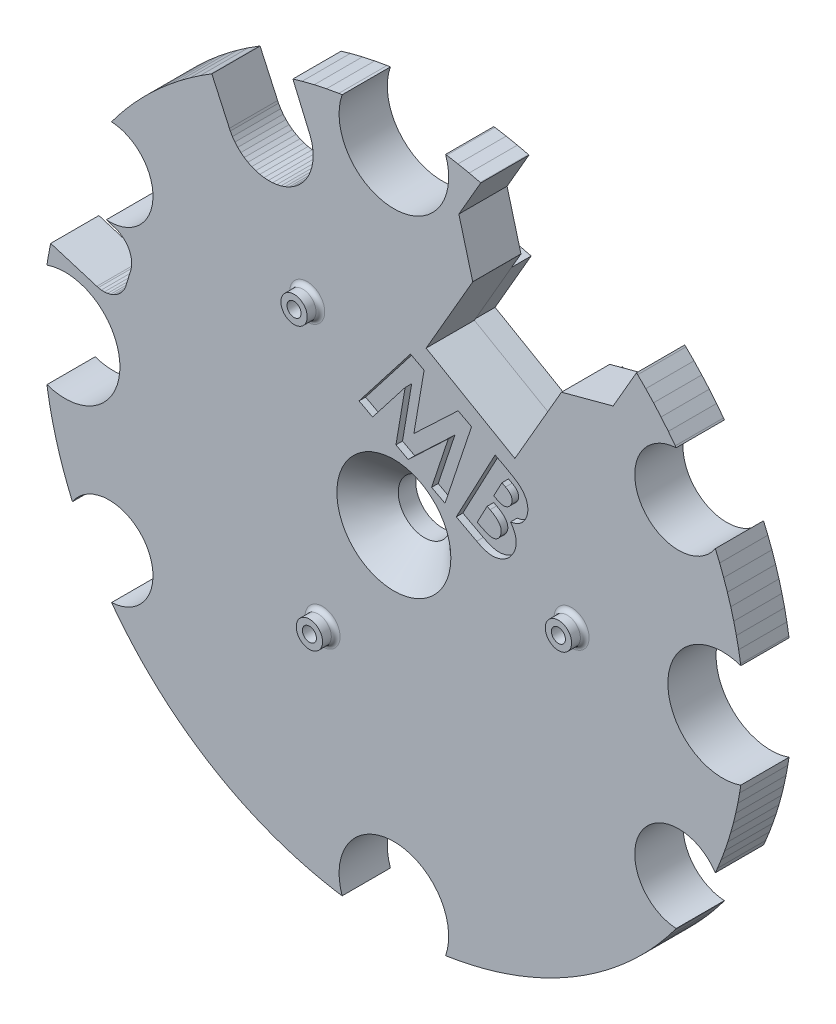
SolidWorks part; units mm, degrees
ref_plane "Płaszczyzna przednia" through (0, 0, 0) normal (0, 0, 1) x (1, 0, 0)
ref_plane "Płaszczyzna górna" through (0, 0, 0) normal (0, 1, 0) x (1, 0, 0)
ref_plane "Płaszczyzna prawa" through (0, 0, 0) normal (1, 0, 0) x (0, 0, -1)
sketch "mandaryna sloty " plane through (0, 0, 0) normal (0, 0, 1) x (1, 0, 0)
  line L0 (16.267, -5.639) -> (49.1732, -24.6374)
  line L1 (49.1732, 24.6374) -> (16.267, 5.639)
  line L2 (13.017, 11.2682) -> (45.9232, 30.2665)
  line L3 (3.25, 54.9039) -> (3.25, 16.9072)
  line L4 (-3.25, 16.9072) -> (-3.25, 54.9039)
  line L5 (-45.9232, 30.2665) -> (-13.017, 11.2682)
  line L6 (37.2705, 55.4531) -> (37.2682, 55.4521) construction
  line L7 (47.1514, 32.7352) -> (37.2705, 55.4531) construction
  line L8 (13.142, 11.0517) -> (46.0605, 30.0571) construction
  line L9 (3, 54.9181) -> (3, 16.9072) construction
  line L10 (29.3889, 60.0012) -> (29.3886, 60.0037) construction
  line L11 (49.0605, 24.861) -> (16.142, 5.8555) construction
  line L12 (60.689, -29.3106) -> (66.5056, -28.6485) construction
  line L13 (16.142, -5.8555) -> (49.0605, -24.861) construction
  line L14 (-16.267, 5.639) -> (-49.1732, 24.6374)
  line L15 (-49.1732, -24.6374) -> (-16.267, -5.639)
  line L16 (46.0605, -30.0571) -> (13.142, -11.0517) construction
  line L17 (58.0631, -43.2712) -> (55.7282, -37.9029) construction
  line L18 (3, -16.9072) -> (3, -54.9181) construction
  line L19 (-13.017, -11.2682) -> (-45.9232, -30.2665)
  line L20 (-3.25, -54.9039) -> (-3.25, -16.9072)
  line L21 (3.25, -16.9072) -> (3.25, -54.9039)
  line L22 (45.9232, -30.2665) -> (13.017, -11.2682)
  line L23 (-29.3886, -60.0037) -> (-4.7738, -57.2019) construction
  line L24 (-29.3889, -60.0012) -> (-29.3886, -60.0037) construction
  line L25 (-37.2705, -55.4531) -> (-37.2682, -55.4521) construction
  line L26 (-47.1514, -32.7352) -> (-37.2705, -55.4531) construction
  line L27 (-60.689, 29.3106) -> (-66.5056, 28.6485) construction
  line L28 (-16.142, 5.8555) -> (-49.0605, 24.861) construction
  line L29 (-46.0605, 30.0571) -> (-13.142, 11.0517) construction
  line L30 (-58.0631, 43.2712) -> (-55.7282, 37.9029) construction
  line L31 (-3, 16.9072) -> (-3, 54.9181) construction
  line L37 (15.3138, 52.8251) -> (7.087, 38.5758)
  line L38 (7.087, 38.5758) -> (27.6707, 26.6918)
  line L39 (27.6707, 26.6918) -> (36.1779, 41.4266)
  circle A0 centre (0, 0) radius 85 construction
  circle A1 centre (0, 0) radius 6 construction
  arc A2 (16.267, 5.639) -> (16.267, -5.639) centre (19.5227, 0) ccw
  arc A3 (3.25, 16.9072) -> (13.017, 11.2682) centre (9.7614, 16.9072) ccw
  arc A4 (-13.017, 11.2682) -> (-3.25, 16.9072) centre (-9.7614, 16.9072) ccw
  arc A5 (46.3174, 30.2054) -> (47.1514, 32.7352) centre (45.3174, 31.9375) ccw construction
  arc A6 (3, 16.9072) -> (13.142, 11.0517) centre (9.7614, 16.9072) ccw construction
  arc A7 (29.3889, 60.0012) -> (31.8898, 56.2177) centre (34.3568, 60.5667) ccw construction
  arc A8 (32.7411, 55.7262) -> (31.8898, 56.2177) centre (0, 0) ccw construction
  arc A9 (32.7411, 55.7262) -> (37.2682, 55.4521) centre (35.2739, 60.0372) ccw construction
  arc A10 (73.76, 25.3667) -> (59.3035, 30.7748) centre (64.3035, 22.1146) ccw construction
  arc A11 (74.9885, -21.4645) -> (73.76, 25.3667) centre (0, 0) ccw construction
  arc A12 (66.5056, -28.6485) -> (74.9885, -21.4645) centre (65.3746, -18.7127) ccw construction
  arc A13 (54.558, -28.035) -> (60.689, -29.3106) centre (59.558, -19.3747) ccw construction
  arc A14 (16.142, 5.8555) -> (16.142, -5.8555) centre (19.5227, 0) ccw construction
  arc A15 (-16.267, -5.639) -> (-16.267, 5.639) centre (-19.5227, 0) ccw
  arc A16 (55.7282, -37.9029) -> (51.558, -33.2312) centre (46.558, -41.8914) ccw construction
  arc A17 (56.0831, -54.2097) -> (58.0631, -43.2712) centre (48.8929, -47.2597) ccw construction
  arc A18 (14.9118, -76.5613) -> (56.0831, -54.2097) centre (0, 0) ccw construction
  arc A19 (3, -66.7458) -> (14.9118, -76.5613) centre (13, -66.7458) ccw construction
  arc A20 (13.142, -11.0517) -> (3, -16.9072) centre (9.7614, -16.9072) ccw construction
  arc A21 (-3.25, -16.9072) -> (-13.017, -11.2682) centre (-9.7614, -16.9072) ccw
  arc A22 (-29.3889, -60.0012) -> (-31.8898, -56.2177) centre (-34.3568, -60.5667) ccw construction
  arc A23 (-32.7411, -55.7262) -> (-31.8898, -56.2177) centre (0, 0) ccw construction
  arc A24 (-32.7411, -55.7262) -> (-37.2682, -55.4521) centre (-35.2739, -60.0372) ccw construction
  arc A25 (-46.3174, -30.2054) -> (-47.1514, -32.7352) centre (-45.3174, -31.9375) ccw construction
  arc A26 (-3, -16.9072) -> (-13.142, -11.0517) centre (-9.7614, -16.9072) ccw construction
  arc A27 (13.017, -11.2682) -> (3.25, -16.9072) centre (9.7614, -16.9072) ccw
  arc A28 (3.25, -54.9039) -> (45.9232, -30.2665) centre (0, 0) ccw
  arc A29 (45.9232, 30.2665) -> (36.1779, 41.4266) centre (0, 0) ccw
  arc A30 (-73.76, -25.3667) -> (-59.3035, -30.7748) centre (-64.3035, -22.1146) ccw construction
  arc A31 (-74.9885, 21.4645) -> (-73.76, -25.3667) centre (0, 0) ccw construction
  arc A32 (-66.5056, 28.6485) -> (-74.9885, 21.4645) centre (-65.3746, 18.7127) ccw construction
  arc A33 (-54.558, 28.035) -> (-60.689, 29.3106) centre (-59.558, 19.3747) ccw construction
  arc A34 (-16.142, -5.8555) -> (-16.142, 5.8555) centre (-19.5227, 0) ccw construction
  arc A35 (-3.25, 54.9039) -> (-45.9232, 30.2665) centre (0, 0) ccw
  arc A36 (-49.1732, 24.6374) -> (-49.1732, -24.6374) centre (0, 0) ccw
  arc A37 (-45.9232, -30.2665) -> (-3.25, -54.9039) centre (0, 0) ccw
  arc A38 (49.1732, -24.6374) -> (49.1732, 24.6374) centre (0, 0) ccw
  arc A39 (-55.7282, 37.9029) -> (-51.558, 33.2312) centre (-46.558, 41.8914) ccw construction
  arc A40 (-56.0831, 54.2097) -> (-58.0631, 43.2712) centre (-48.8929, 47.2597) ccw construction
  arc A41 (-14.9118, 76.5613) -> (-56.0831, 54.2097) centre (0, 0) ccw construction
  arc A42 (-3, 66.7458) -> (-14.9118, 76.5613) centre (-13, 66.7458) ccw construction
  arc A43 (-13.142, 11.0517) -> (-3, 16.9072) centre (-9.7614, 16.9072) ccw construction
  arc A44 (15.3138, 52.8251) -> (3.25, 54.9039) centre (0, 0) ccw
extrude "sloty_mandaryna" add sketch "mandaryna sloty " along normal blind 5
sketch "szkic Koslau" plane through (0, 0, 0) normal (0, 0, 1) x (1, 0, 0)
  line L0 (0, 0) -> (75, 0) construction
  line L1 (0, 0) -> (83.812, 48.3889) construction
  line L2 (0, 0) -> (80.3963, -46.4168) construction
  line L3 (-16.27, -28.1805) -> (0, 0) construction
  line L4 (0, 0) -> (40.54, 0) construction
  line L5 (-19.77, 34.2427) -> (0, 0) construction
  line L6 (-65.6121, 27.5218) -> (-63.6026, 26.9075)
  line L664 (-41.5257, 68.3953) -> (-41.7981, 68.2351)
  line L665 (-41.7981, 68.2351) -> (-44.2022, 66.7029)
  line L666 (-44.2022, 66.7029) -> (-46.5503, 65.0859)
  line L667 (-46.5503, 65.0859) -> (-48.8393, 63.3864)
  line L668 (-48.8393, 63.3864) -> (-51.0663, 61.6064)
  line L669 (-51.0663, 61.6064) -> (-53.2284, 59.7481)
  line L670 (-53.2284, 59.7481) -> (-55.323, 57.8141)
  line L671 (-55.323, 57.8141) -> (-57.3474, 55.8066)
  line L672 (-57.3474, 55.8066) -> (-59.299, 53.7284)
  line L673 (-59.299, 53.7284) -> (-61.1753, 51.5819)
  line L674 (-61.1753, 51.5819) -> (-62.974, 49.3699)
  line L675 (-62.974, 49.3699) -> (-64.3985, 47.4847)
  line L684 (-63.6026, 26.9075) -> (-63.2677, 26.8051)
  line L685 (-63.2677, 26.8051) -> (-62.6302, 26.5146)
  line L686 (-62.6302, 26.5146) -> (-62.0361, 26.1433)
  line L687 (-62.0361, 26.1433) -> (-61.4956, 25.6977)
  line L688 (-61.4956, 25.6977) -> (-61.0178, 25.1854)
  line L689 (-61.0178, 25.1854) -> (-60.611, 24.6151)
  line L690 (-60.611, 24.6151) -> (-60.2822, 23.9966)
  line L691 (-60.2822, 23.9966) -> (-60.0368, 23.3404)
  line L692 (-60.0368, 23.3404) -> (-59.8793, 22.6578)
  line L693 (-59.8793, 22.6578) -> (-59.8121, 21.9605)
  line L694 (-59.8121, 21.9605) -> (-59.8366, 21.2604)
  line L695 (-59.8366, 21.2604) -> (-59.9522, 20.5695)
  line L696 (-59.9522, 20.5695) -> (-60.0546, 20.2345)
  line L697 (-60.0546, 20.2345) -> (-61.0884, 16.853)
  line L698 (-61.0884, 16.853) -> (-61.1908, 16.5181)
  line L699 (-61.1908, 16.5181) -> (-61.4813, 15.8806)
  line L700 (-61.4813, 15.8806) -> (-61.8525, 15.2866)
  line L701 (-61.8525, 15.2866) -> (-62.2981, 14.746)
  line L702 (-62.2981, 14.746) -> (-62.8105, 14.2682)
  line L703 (-62.8105, 14.2682) -> (-63.3808, 13.8614)
  line L704 (-63.3808, 13.8614) -> (-63.9993, 13.5326)
  line L705 (-63.9993, 13.5326) -> (-64.6555, 13.2872)
  line L706 (-64.6555, 13.2872) -> (-65.3381, 13.1297)
  line L707 (-65.3381, 13.1297) -> (-66.0354, 13.0625)
  line L708 (-66.0354, 13.0625) -> (-66.7355, 13.087)
  line L709 (-66.7355, 13.087) -> (-67.4264, 13.2026)
  line L710 (-67.4264, 13.2026) -> (-67.7613, 13.305)
  line L711 (-67.7613, 13.305) -> (-78.2874, 16.5231)
  line L712 (-78.2874, 16.5231) -> (-78.3972, 16.0307)
  line L713 (-78.3972, 16.0307) -> (-78.9185, 13.2278)
  line L714 (-78.9185, 13.2278) -> (-79.1322, 11.7972)
  line L747 (-79.1323, -11.7972) -> (-78.9443, -13.072)
  line L748 (-78.9443, -13.072) -> (-78.4336, -15.8507)
  line L749 (-78.4336, -15.8507) -> (-77.8251, -18.6098)
  line L750 (-77.8251, -18.6098) -> (-77.1196, -21.3456)
  line L751 (-77.1196, -21.3456) -> (-76.318, -24.0548)
  line L752 (-76.318, -24.0548) -> (-75.4212, -26.734)
  line L753 (-75.4212, -26.734) -> (-74.4305, -29.3799)
  line L754 (-74.4305, -29.3799) -> (-73.3469, -31.9892)
  line L755 (-73.3469, -31.9892) -> (-73.3262, -32.0345)
  line L761 (-64.3933, -47.4844) -> (-63.2913, -48.9621)
  line L762 (-63.2913, -48.9621) -> (-61.5233, -51.1659)
  line L763 (-61.5233, -51.1659) -> (-59.6787, -53.306)
  line L764 (-59.6787, -53.306) -> (-57.7597, -55.3795)
  line L765 (-57.7597, -55.3795) -> (-55.7686, -57.3841)
  line L766 (-55.7686, -57.3841) -> (-53.7081, -59.3171)
  line L767 (-53.7081, -59.3171) -> (-51.5805, -61.1762)
  line L768 (-51.5805, -61.1762) -> (-49.3887, -62.9589)
  line L769 (-49.3887, -62.9589) -> (-47.1353, -64.6632)
  line L770 (-47.1353, -64.6632) -> (-44.8231, -66.2869)
  line L771 (-44.8231, -66.2869) -> (-42.4551, -67.828)
  line L772 (-42.4551, -67.828) -> (-40.0341, -69.2845)
  line L773 (-40.0341, -69.2845) -> (-37.5633, -70.6546)
  line L774 (-37.5633, -70.6546) -> (-35.0456, -71.9366)
  line L775 (-35.0456, -71.9366) -> (-32.4842, -73.129)
  line L776 (-32.4842, -73.129) -> (-29.8823, -74.2302)
  line L777 (-29.8823, -74.2302) -> (-27.2431, -75.2389)
  line L778 (-27.2431, -75.2389) -> (-24.57, -76.1537)
  line L779 (-24.57, -76.1537) -> (-21.8663, -76.9736)
  line L780 (-21.8663, -76.9736) -> (-19.1353, -77.6976)
  line L781 (-19.1353, -77.6976) -> (-16.3804, -78.3247)
  line L782 (-16.3804, -78.3247) -> (-13.6052, -78.8541)
  line L783 (-13.6052, -78.8541) -> (-11.7968, -79.1333)
  line L816 (11.7955, -79.1372) -> (12.3223, -79.0645)
  line L817 (12.3223, -79.0645) -> (15.0818, -78.5848)
  line L818 (15.0818, -78.5848) -> (17.8227, -78.0089)
  line L819 (17.8227, -78.0089) -> (20.5418, -77.3374)
  line L820 (20.5418, -77.3374) -> (23.2358, -76.5711)
  line L821 (23.2358, -76.5711) -> (25.9012, -75.7111)
  line L822 (25.9012, -75.7111) -> (28.535, -74.7582)
  line L823 (28.535, -74.7582) -> (31.1338, -73.7138)
  line L824 (31.1338, -73.7138) -> (33.6944, -72.5791)
  line L825 (33.6944, -72.5791) -> (36.2138, -71.3554)
  line L826 (36.2138, -71.3554) -> (38.6888, -70.0444)
  line L827 (38.6888, -70.0444) -> (41.1164, -68.6475)
  line L828 (41.1164, -68.6475) -> (43.4936, -67.1665)
  line L829 (43.4936, -67.1665) -> (45.8175, -65.6033)
  line L830 (45.8175, -65.6033) -> (48.0854, -63.9596)
  line L831 (48.0854, -63.9596) -> (50.2943, -62.2376)
  line L832 (50.2943, -62.2376) -> (52.4415, -60.4394)
  line L833 (52.4415, -60.4394) -> (54.5246, -58.5671)
  line L834 (54.5246, -58.5671) -> (56.5408, -56.6231)
  line L835 (56.5408, -56.6231) -> (58.4878, -54.6097)
  line L836 (58.4878, -54.6097) -> (60.3631, -52.5294)
  line L837 (60.3631, -52.5294) -> (62.1645, -50.3847)
  line L838 (62.1645, -50.3847) -> (63.8897, -48.1783)
  line L839 (63.8897, -48.1783) -> (64.3941, -47.4844)
  line L847 (73.3186, -32.023) -> (73.82, -30.8703)
  line L848 (73.82, -30.8703) -> (74.665, -28.7664)
  line L849 (74.665, -28.7664) -> (75.45, -26.6393)
  line L850 (75.45, -26.6393) -> (76.1745, -24.4909)
  line L851 (76.1745, -24.4909) -> (76.8378, -22.3228)
  line L852 (76.8378, -22.3228) -> (77.4395, -20.1368)
  line L853 (77.4395, -20.1368) -> (77.9789, -17.9346)
  line L854 (77.9789, -17.9346) -> (78.4558, -15.718)
  line L855 (78.4558, -15.718) -> (78.8696, -13.4888)
  line L856 (78.8696, -13.4888) -> (79.1344, -11.7965)
  line L889 (79.138, 11.7952) -> (79.0885, 12.1564)
  line L890 (79.0885, 12.1564) -> (78.6519, 14.719)
  line L891 (78.6519, 14.719) -> (78.1322, 17.2661)
  line L892 (78.1322, 17.2661) -> (77.5302, 19.7949)
  line L893 (77.5302, 19.7949) -> (76.8463, 22.3029)
  line L894 (76.8463, 22.3029) -> (76.0812, 24.7873)
  line L895 (76.0812, 24.7873) -> (75.2359, 27.2456)
  line L896 (75.2359, 27.2456) -> (74.3112, 29.6751)
  line L897 (74.3112, 29.6751) -> (73.325, 32.0327)
  line L904 (64.3985, 47.4847) -> (64.1891, 47.7758)
  line L905 (64.1891, 47.7758) -> (62.6033, 49.8356)
  line L906 (62.6033, 49.8356) -> (60.9515, 51.8429)
  line L907 (60.9515, 51.8429) -> (59.2353, 53.7954)
  line L908 (59.2353, 53.7954) -> (57.4566, 55.6911)
  line L909 (57.4566, 55.6911) -> (55.6173, 57.5281)
  line L910 (55.6173, 57.5281) -> (55.3487, 57.7795)
  line L911 (55.3487, 57.7795) -> (50.0191, 48.5483)
  line L912 (50.0191, 48.5483) -> (38.2358, 45.391)
  line L913 (38.2358, 45.391) -> (27.5975, 26.965)
  line L914 (27.5975, 26.965) -> (7.3602, 38.649)
  line L915 (7.3602, 38.649) -> (17.9935, 57.0663)
  line L916 (17.9935, 57.0663) -> (17.9848, 57.0713)
  line L917 (17.9848, 57.0713) -> (14.8238, 68.8683)
  line L918 (14.8238, 68.8683) -> (19.8199, 77.5217)
  line L919 (19.8199, 77.5217) -> (19.6954, 77.5555)
  line L920 (19.6954, 77.5555) -> (17.1657, 78.1544)
  line L921 (17.1657, 78.1544) -> (14.618, 78.6707)
  line L922 (14.618, 78.6707) -> (12.0548, 79.104)
  line L923 (12.0548, 79.104) -> (11.7947, 79.1394)
  line L956 (-11.7963, 79.135) -> (-12.5646, 79.0268)
  line L957 (-12.5646, 79.0268) -> (-15.3717, 78.5291)
  line L958 (-15.3717, 78.5291) -> (-18.1594, 77.9317)
  line L959 (-18.1594, 77.9317) -> (-20.924, 77.2353)
  line L960 (-20.924, 77.2353) -> (-23.04, 76.6214)
  line L961 (-23.04, 76.6214) -> (-19.2348, 67.738)
  line L962 (-19.2348, 67.738) -> (-19.0427, 67.2899)
  line L963 (-19.0427, 67.2899) -> (-18.7473, 66.3607)
  line L964 (-18.7473, 66.3607) -> (-18.5437, 65.4071)
  line L965 (-18.5437, 65.4071) -> (-18.4339, 64.4382)
  line L966 (-18.4339, 64.4382) -> (-18.4188, 63.4633)
  line L967 (-18.4188, 63.4633) -> (-18.4987, 62.4915)
  line L968 (-18.4987, 62.4915) -> (-18.6727, 61.5321)
  line L969 (-18.6727, 61.5321) -> (-18.9392, 60.5942)
  line L970 (-18.9392, 60.5942) -> (-19.2956, 59.6866)
  line L971 (-19.2956, 59.6866) -> (-19.7387, 58.818)
  line L972 (-19.7387, 58.818) -> (-20.2641, 57.9966)
  line L973 (-20.2641, 57.9966) -> (-20.867, 57.2303)
  line L974 (-20.867, 57.2303) -> (-21.5415, 56.5262)
  line L975 (-21.5415, 56.5262) -> (-22.2814, 55.8911)
  line L976 (-22.2814, 55.8911) -> (-23.0795, 55.3309)
  line L977 (-23.0795, 55.3309) -> (-23.9283, 54.851)
  line L978 (-23.9283, 54.851) -> (-24.8198, 54.456)
  line L979 (-24.8198, 54.456) -> (-25.7454, 54.1496)
  line L980 (-25.7454, 54.1496) -> (-26.6965, 53.9347)
  line L981 (-26.6965, 53.9347) -> (-27.664, 53.8133)
  line L982 (-27.664, 53.8133) -> (-28.6387, 53.7866)
  line L983 (-28.6387, 53.7866) -> (-29.6114, 53.8548)
  line L984 (-29.6114, 53.8548) -> (-30.5728, 54.0174)
  line L985 (-30.5728, 54.0174) -> (-31.5138, 54.2727)
  line L986 (-31.5138, 54.2727) -> (-32.4256, 54.6183)
  line L987 (-32.4256, 54.6183) -> (-33.2994, 55.0509)
  line L988 (-33.2994, 55.0509) -> (-34.127, 55.5666)
  line L989 (-34.127, 55.5666) -> (-34.9005, 56.1602)
  line L990 (-34.9005, 56.1602) -> (-35.6126, 56.8263)
  line L991 (-35.6126, 56.8263) -> (-36.2565, 57.5585)
  line L992 (-36.2565, 57.5585) -> (-36.8261, 58.3499)
  line L993 (-36.8261, 58.3499) -> (-37.316, 59.1929)
  line L994 (-37.316, 59.1929) -> (-37.5189, 59.6363)
  line L995 (-37.5189, 59.6363) -> (-41.5257, 68.3953)
  arc A0 (79.138, 11.7952) -> (79.1344, -11.7965) centre (75, 0) ccw
  arc A1 (11.7955, -79.1372) -> (-11.7968, -79.1333) centre (0, -75) ccw
  arc A2 (-79.1323, -11.7972) -> (-79.1322, 11.7972) centre (-75, 0) ccw
  circle A3 centre (40.54, 0) radius 1.6 construction
  circle A4 centre (-16.27, -28.1805) radius 1.6 construction
  circle A5 centre (-19.77, 34.2427) radius 1.6 construction
  circle A6 centre (0, 0) radius 75 construction
  circle A7 centre (75, 0) radius 5.4933 construction
  arc A8 (-11.7963, 79.135) -> (11.7947, 79.1394) centre (0, 75) ccw
  arc A9 (64.3985, 47.4847) -> (73.325, 32.0327) centre (64.9519, 37.5) ccw
  arc A10 (73.3186, -32.023) -> (64.3941, -47.4844) centre (64.9519, -37.5) ccw
  arc A11 (-64.3933, -47.4844) -> (-73.3262, -32.0345) centre (-64.9519, -37.5) ccw
  arc A12 (-65.6121, 27.5218) -> (-64.3985, 47.4847) centre (-64.9519, 37.5) ccw
  point P2 (0, 0)
  point P44 (0, 0)
  point P66 (0, 0)
  dimension "D1" = 150
  dimension "D2" = 25
  dimension "D6" = 20
  dimension "D7" = 20
  dimension "D4" = 30
  dimension "D5" = 30
  dimension "D3" = 4
  dimension "D8" = 2
extrude "Boss-Extrude2" add sketch "szkic Koslau" along normal blind 11 from surface at 5 starting at face at (-16.6814, 28.8931, 5)
sketch "obrys " plane through (0, 0, 0) normal (0, 0, 1) x (1, 0, 0)
  line L0 (-11.1033, -19.6081) -> (0, 0) construction
  line L1 (-19.5342, 34.3777) -> (0, 0) construction
  line L2 (15.4295, 0) -> (40.54, 0) construction
  line L9 (55.5497, 57.5863) -> (50.3316, 48.5483)
  line L10 (50.3316, 48.5483) -> (38.5483, 45.391)
  line L11 (38.5483, 45.391) -> (27.9101, 26.965)
  line L12 (27.9101, 26.965) -> (7.6728, 38.649)
  line L13 (7.6728, 38.649) -> (18.306, 57.0663)
  line L14 (18.306, 57.0663) -> (15.1364, 68.8683)
  line L15 (15.1364, 68.8683) -> (19.9661, 77.481)
  line L20 (-22.7275, 76.6214) -> (-19.099, 68.1275)
  line L21 (-41.2132, 68.3953) -> (-37.3042, 59.8245)
  line L23 (-69.1635, 28.7032) -> (-63.4698, 26.9624)
  line L24 (-77.9736, 16.5229) -> (-67.6319, 13.361)
  line L31 (-22.7275, 76.6214) -> (-22.7534, 76.7087)
  line L32 (-41.2132, 68.3953) -> (-41.2692, 68.5478)
  line L34 (-77.9736, 16.5229) -> (-78.2701, 16.6056)
  arc A3 (-37.3042, 59.8245) -> (-19.099, 68.1275) centre (-28.1209, 63.799) ccw
  arc A4 (-67.6319, 13.361) -> (-63.4698, 26.9624) centre (-65.4598, 20.1338) ccw
  arc A9 (19.9661, 77.481) -> (9.2623, 79.4742) centre (0, 0) ccw
  arc A10 (-8.5995, 79.5487) -> (-22.7534, 76.7087) centre (0, 0) ccw
  arc A11 (-41.2692, 68.5478) -> (-63.3493, 48.8755) centre (0, 0) ccw
  arc A12 (-78.2701, 16.6056) -> (-79.5323, 8.7499) centre (0, 0) ccw
  arc A13 (-79.5323, -8.7498) -> (-73.8796, -30.7205) centre (0, 0) ccw
  arc A14 (9.26, -79.4745) -> (63.511, -48.6652) centre (0, 0) ccw
  arc A15 (79.494, 9.0915) -> (74.0222, 30.3753) centre (0, 0) ccw
  arc A16 (74.0222, -30.3753) -> (63.511, -48.6652) centre (68.1121, -39.1441) ccw
  arc A18 (-63.3493, -48.8755) -> (-73.8796, -30.7205) centre (-67.487, -39.1441) ccw
  arc A21 (63.511, 48.6652) -> (74.0222, 30.3753) centre (68.1121, 39.1441) ccw
  circle A22 centre (0.3125, -78.2882) radius 10.5746 [skipped]
  circle A23 centre (0.3125, 78.2882) radius 10.5746 [skipped]
  arc A24 (63.511, 48.6652) -> (55.5497, 57.5863) centre (0, 0) ccw
  arc A25 (74.0222, -30.3753) -> (79.4939, -9.0923) centre (0, 0) ccw
  arc A26 (-63.3493, -48.8755) -> (-8.5996, -79.5487) centre (0, 0) ccw
  arc A27 (-8.5995, 79.5487) -> (9.2623, 79.4742) centre (0.3127, 75.0129) ccw
  arc A28 (-69.1635, 28.7032) -> (-63.3493, 48.8755) centre (-67.487, 39.1441) ccw
  arc A29 (-74.0727, 30.8706) -> (-72.1882, 29.672) centre (-67.487, 39.1441) ccw [skipped]
  arc A30 (79.494, 9.0915) -> (79.4939, -9.0923) centre (75.3301, -0.0004) ccw
  arc A31 (9.26, -79.4745) -> (-8.5996, -79.5487) centre (0.3115, -75.0109) ccw
  arc A32 (-79.5323, -8.7498) -> (-79.5323, 8.7499) centre (-74.6908, 0) ccw
  point P46 (0.3125, 0)
  dimension "D8" = 20.013
  dimension "D9" = 14.2253
  dimension "D11" = 160.0243
  dimension "D12" = 20
  dimension "D3" = 80.0122
  dimension "D5" = 20
  dimension "D14" = 20
  dimension "D16" = 20
  dimension "D2" = 39.54
  dimension "D4" = 6
  dimension "D13" = 40.54
  dimension "D15" = 39.54
sketch "otwory " plane through (0, 0, 0) normal (0, 0, 1) x (1, 0, 0)
  line L0 (-16.27, -28.1805) -> (0, 0) construction
  line L1 (-19.77, 34.2427) -> (0, 0) construction
  line L2 (0, 0) -> (40.54, 0) construction
  line L7 (0, 0) -> (0, 28.2911) construction
  circle A0 centre (-19.77, 34.2427) radius 3
  circle A1 centre (40.54, 0) radius 3
  circle A2 centre (-16.27, -28.1805) radius 3
  circle A3 centre (-19.77, 34.2427) radius 1.6
  circle A4 centre (40.54, 0) radius 1.6
  circle A5 centre (-16.27, -28.1805) radius 1.6
  dimension "D5" = 6
  dimension "D10" = 6
  dimension "D11" = 6
  dimension "D12" = 3.2
  dimension "D13" = 3.2
  dimension "D14" = 3.2
  dimension "D1" = 120
  dimension "D2" = 39.54
  dimension "D3" = 40.54
  dimension "D4" = 32.54
  dimension "D6" = 40.54
  dimension "D7" = 39.54
  dimension "D8" = 32.54
  dimension "D9" = 120
extrude "Boss-Extrude3" add sketch "otwory " along normal blind 3 from surface at 16 starting at face at (-11.6336, 8.3546, 16)
sketch "Sketch3" plane through (0, 0, 19) normal (0, 0, 1) x (1, 0, 0)
  circle A0 centre (-16.27, -28.1805) radius 1.6 construction
  circle A1 centre (40.54, 0) radius 1.6 construction
  circle A2 centre (-19.77, 34.2427) radius 1.6 construction
  circle A3 centre (-16.27, -28.1805) radius 1.6
  circle A4 centre (40.54, 0) radius 1.6
  circle A5 centre (-19.77, 34.2427) radius 1.6
extrude "Cut-Extrude1" cut sketch "Sketch3" against normal through all
sketch "Sketch4" plane through (0, 0, 16) normal (0, 0, 1) x (1, 0, 0)
  circle A0 centre (0, 0) radius 6
  dimension "D1" = 12
extrude "Cut-Extrude2" cut sketch "Sketch4" against normal through all
chamfer "Chamfer1" distance 7 angle 45 1 edges at (6, 0, 16)
sketch "Sketch6" plane through (0, 0, 16) normal (0, 0, 1) x (1, 0, 0)
  line L0 (17.4789, 32.807) -> (6.1127, 11.4732) construction
  line L1 (7.3602, 38.649) -> (27.5975, 26.965) construction
  line L2 (-8.5817, 20.9068) -> (22.139, 4.5395) construction
  circle A0 centre (0, 0) radius 13 construction
  text T0 "MB" font "Century Gothic" height in points 72
  point P9 (6.7786, 12.7232)
extrude "Cut-Extrude3" cut sketch "Sketch6" against normal blind 1.5
fillet "Fillet1" radius 1 3 edges at (-13.27, -28.1805, 16) (43.54, 0, 16) (-16.77, 34.2427, 16)
